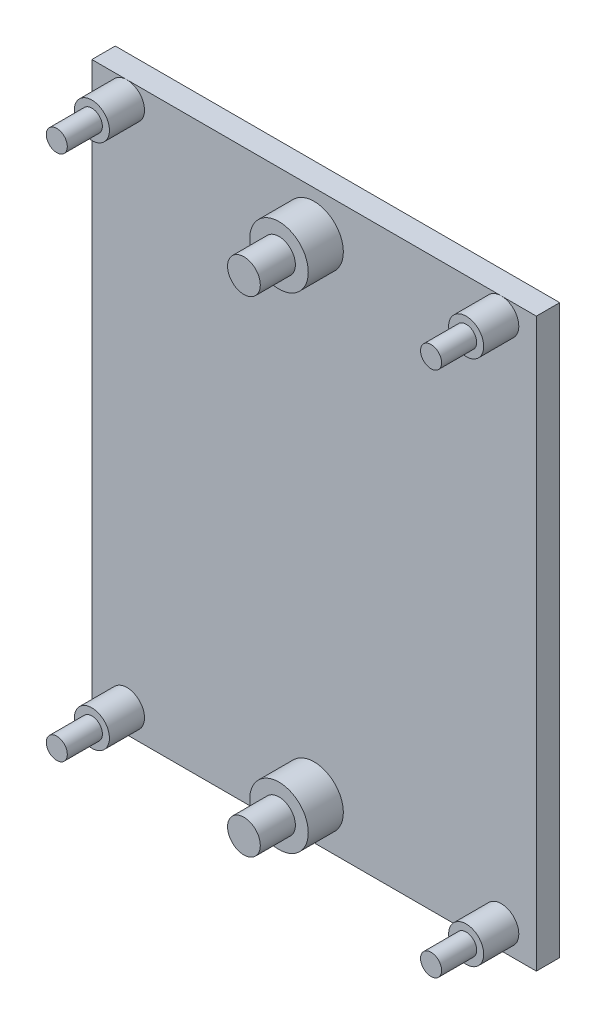
SolidWorks part; units mm, degrees
ref_plane "Ebene vorne" through (0, 0, 0) normal (1, 0, 0) x (0, 1, 0)
ref_plane "Ebene oben" through (0, 0, 0) normal (0, 0, 1) x (0, 1, 0)
ref_plane "Ebene rechts" through (0, 0, 0) normal (0, 1, 0) x (-1, 0, 0)
sketch "Skizze1" plane through (0, 0, 0) normal (0, 0, 1) x (0, 1, 0)
  line L1 (-24.25, -19) -> (24.25, -19)
  line L2 (-24.25, -19) -> (-24.25, 19)
  line L3 (-24.25, 19) -> (24.25, 19)
  line L4 (24.25, -19) -> (24.25, 19)
  line L5 (-24.25, -19) -> (24.25, 19) construction
  line L6 (-24.25, 19) -> (24.25, -19) construction
  point P0 (0, 0)
  dimension "D1" = 38
  dimension "D2" = 48.5
extrude "Aufsatz-Linear austragen1" add sketch "Skizze1" along normal blind 2 contours L2 L3 L4 L1
sketch "Skizze2" plane through (0, 0, 2) normal (0, 0, 1) x (1, 0, 0)
  circle A0 centre (-16, -22.25) radius 1.5
  circle A1 centre (16, -22.25) radius 1.5
  circle A2 centre (16, 22.75) radius 1.5
  circle A3 centre (-16, 22.75) radius 1.5
  circle A4 centre (0, 20.75) radius 2.5
  circle A5 centre (0, -20.75) radius 2.5
  dimension "D1" = 3
  dimension "D4" = 3
  dimension "D7" = 3
  dimension "D12" = 3
  dimension "D15" = 5
  dimension "D18" = 5
  dimension "D2" = 1.5
  dimension "D3" = 3
  dimension "D5" = 3
  dimension "D6" = 1.5
  dimension "D8" = 3
  dimension "D9" = 2
  dimension "D10" = 2
  dimension "D11" = 3
  dimension "D13" = 19
  dimension "D14" = 3.5
  dimension "D16" = 19
  dimension "D17" = 3.5
  dimension "D19" = 19
  dimension "D20" = 41.5
  dimension "D21" = 16
  dimension "D22" = 16
  dimension "D23" = 16
  dimension "D24" = 16
  dimension "D25" = 45
  dimension "D26" = 45
  dimension "D27" = 2
  dimension "D28" = 1.5
  dimension "D29" = 2
extrude "Aufsatz-Linear austragen2" add sketch "Skizze2" along normal blind 3
sketch "Skizze3" plane through (0, 0, 5) normal (0, 0, 1) x (1, 0, 0)
  circle A0 centre (0, 20.75) radius 1.4
  circle A1 centre (16, 22.75) radius 0.9
  circle A2 centre (-16, 22.75) radius 0.9
  circle A3 centre (0, -20.75) radius 1.4
  circle A4 centre (-16, -22.25) radius 0.9
  circle A5 centre (16, -22.25) radius 0.9
  dimension "D1" = 1.8
  dimension "D2" = 2.8
  dimension "D3" = 1.8
  dimension "D4" = 1.8
  dimension "D5" = 2.8
  dimension "D6" = 1.8
extrude "Aufsatz-Linear austragen3" add sketch "Skizze3" along normal blind 3
